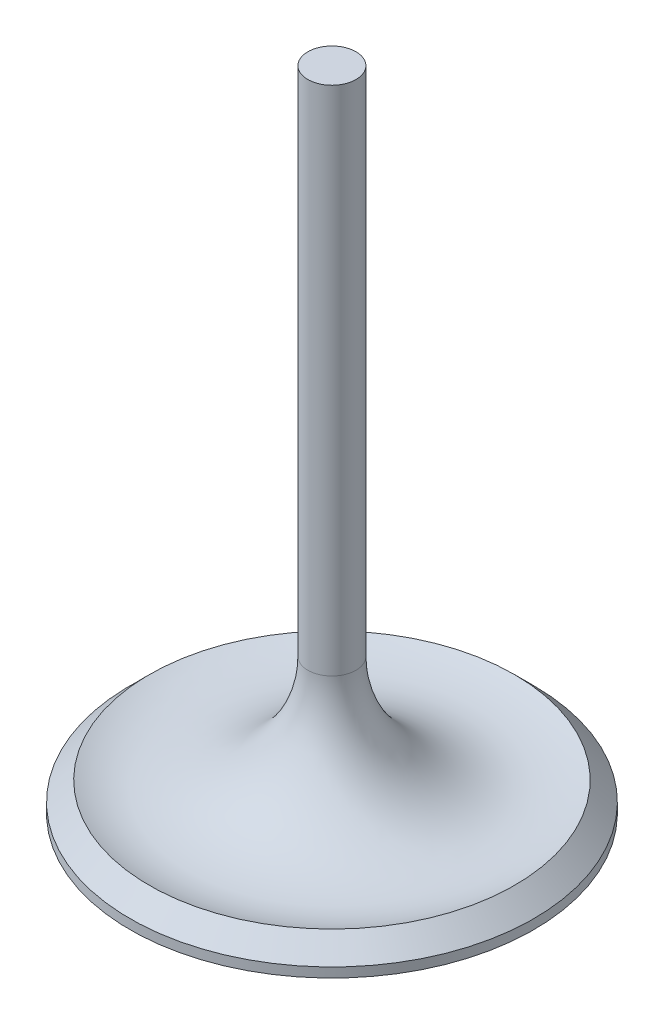
SolidWorks part; units mm, degrees
ref_plane "Front Plane" through (0, 0, 0) normal (0, 0, 1) x (1, 0, 0)
ref_plane "Top Plane" through (0, 0, 0) normal (0, 1, 0) x (1, 0, 0)
ref_plane "Right Plane" through (0, 0, 0) normal (1, 0, 0) x (0, 0, -1)
sketch "Sketch1" plane through (0, 0, 0) normal (0, 0, 1) x (1, 0, 0)
  line L0 (0, 0) -> (0, 85.55)
  line L1 (0, 85.55) -> (3.18, 85.55)
  line L2 (3.18, 85.55) -> (3.18, 17.9547)
  line L3 (24.13, 3.81) -> (26.67, 1.27)
  line L4 (26.67, 1.27) -> (26.67, 0)
  line L5 (26.67, 0) -> (0, 0)
  arc A0 (3.18, 17.9547) -> (24.13, 3.81) centre (18.43, 17.9547) ccw
  dimension "D1" = 85.55
  dimension "D7" = 15.25
  dimension "D2" = 26.67
  dimension "D3" = 3.18
  dimension "D4" = 1.27
  dimension "D5" = 3.81
  dimension "D6" = 45
revolve "Revolve1" add sketch "Sketch1" angle 360 about L0
